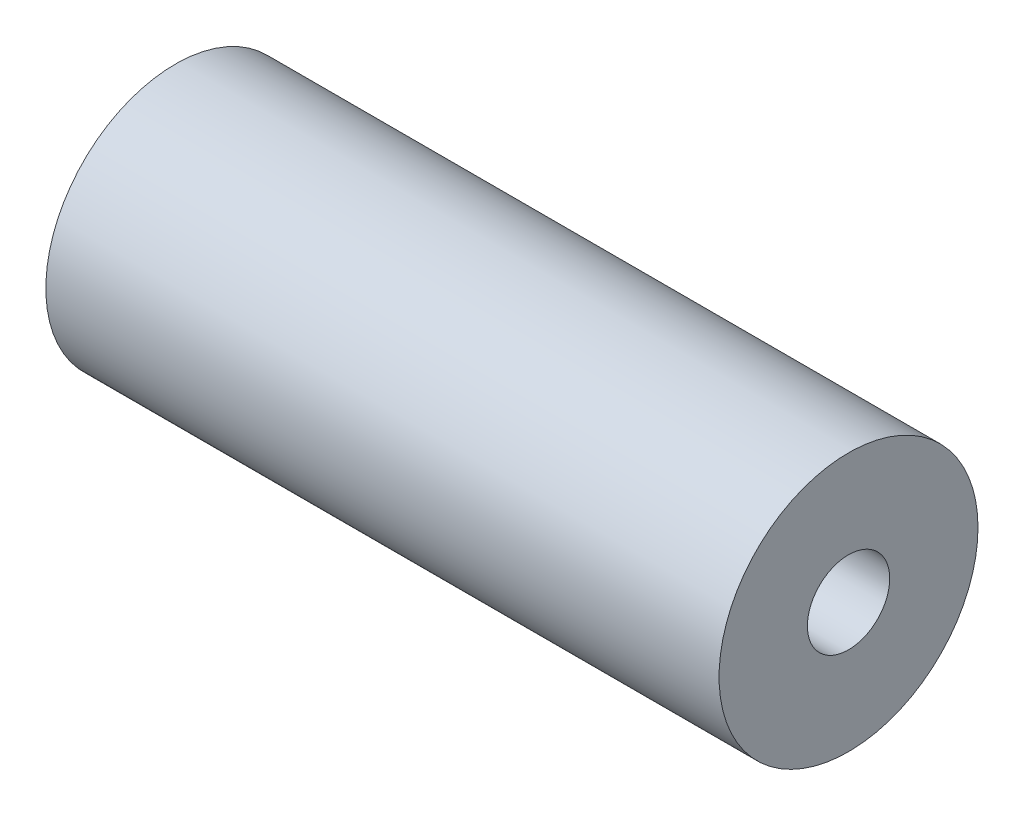
SolidWorks part; units mm, degrees
material "6061-T6 (SS)"
ref_plane "Front Plane" through (0, 0, 0) normal (0, 0, 1) x (1, 0, 0)
ref_plane "Top Plane" through (0, 0, 0) normal (0, 1, 0) x (1, 0, 0)
ref_plane "Right Plane" through (0, 0, 0) normal (1, 0, 0) x (0, 0, -1)
sketch "Sketch1" plane through (0, 0, 0) normal (1, 0, 0) x (0, 0, -1)
  circle A0 centre (0, 0) radius 6.35
  dimension "D1" = 12.7
extrude "Boss-Extrude1" add sketch "Sketch1" along normal mid plane 33.02
hole_wizard "Tap Drill for #10-32 Tap1" positions "Sketch2" profile "Sketch3" hole size "#10-32" standard "ANSI Inch"
sketch "Sketch2" plane through (16.51, 0, 0) normal (1, 0, 0) x (0, 0, -1)
  point P0 (0, 0)
sketch "Sketch3" plane through (16.51, 0, 0) normal (0, 1, 0) x (0, 0, -1)
  line L0 (0, 0) -> (0, 12.6433)
  line L1 (0, 12.6433) -> (2.0193, 11.43)
  line L2 (2.0193, 11.43) -> (2.0193, 0)
  line L5 (2.0193, 0) -> (0, 0)
  line L10 (0, 12.6433) -> (-2.0193, 11.43) construction
  line L11 (0, -6.35) -> (0, 107.95) construction
  dimension "Hole Dia." = 4.0386
  dimension "Hole Depth" = 11.43
  dimension "Drill Angle" = 118
mirror "Mirror1" about plane through (0, 0, 0) normal (1, 0, 0) of "Tap Drill for #10-32 Tap1"
